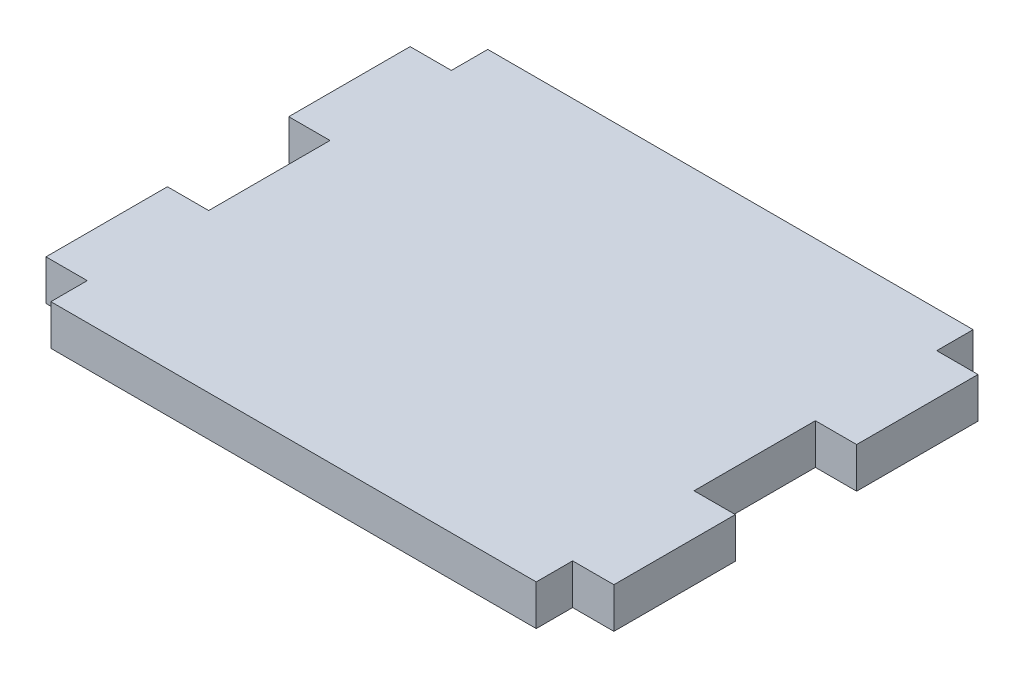
SolidWorks part; units mm, degrees
ref_plane "Front Plane" through (0, 0, 0) normal (0, 0, 1) x (1, 0, 0)
ref_plane "Top Plane" through (0, 0, 0) normal (0, 1, 0) x (1, 0, 0)
ref_plane "Right Plane" through (0, 0, 0) normal (1, 0, 0) x (0, 0, -1)
sketch "Sketch1" plane through (0, 0, 0) normal (1, 0, 0) x (0, 0, -1)
  line L1 (-27.0045, 2.5) -> (27.0045, 2.5)
  line L2 (-27.0045, 2.5) -> (-27.0045, -2.5)
  line L3 (-27.0045, -2.5) -> (27.0045, -2.5)
  line L4 (27.0045, 2.5) -> (27.0045, -2.5)
  line L5 (-27.0045, 2.5) -> (27.0045, -2.5) construction
  line L6 (-27.0045, -2.5) -> (27.0045, 2.5) construction
  point P0 (0, 0)
  dimension "D1" = 5
  dimension "D2" = 54.24
extrude "Boss-Extrude1" add sketch "Sketch1" along normal blind 70.2
sketch "Sketch5" plane through (0, -2.5, 0) normal (0, -1, 0) x (1, 0, 0)
  line L0 (70.2, 27.0045) -> (65.1, 27.0045)
  line L1 (70.2, 27.0045) -> (0, 27.0045) construction
  line L2 (65.1, 27.0045) -> (65.1, 22.5045)
  line L3 (65.1, 22.5045) -> (70.2, 22.5045)
  line L4 (70.2, 27.0045) -> (70.2, -27.0045) construction
  line L5 (70.2, 22.5045) -> (70.2, 27.0045)
  line L6 (70.2, -27.0045) -> (65.1, -27.0045)
  line L7 (70.2, -27.0045) -> (0, -27.0045) construction
  line L8 (65.1, -27.0045) -> (65.1, -22.5045)
  line L9 (65.1, -22.5045) -> (70.2, -22.5045)
  line L10 (70.2, -22.5045) -> (70.2, -27.0045)
  line L11 (70.2, 7.4955) -> (65.1, 7.4955)
  line L12 (65.1, 7.4955) -> (65.1, -7.5045)
  line L13 (65.1, -7.5045) -> (70.2, -7.5045)
  line L14 (70.2, -7.5045) -> (70.2, 7.4955)
  line L16 (5.1, -22.5045) -> (0, -22.5045)
  line L17 (5.1, -27.0045) -> (5.1, -22.5045)
  line L18 (0, -27.0045) -> (5.1, -27.0045)
  line L19 (0, -22.5045) -> (0, -27.0045)
  line L20 (5.1, -7.5045) -> (0, -7.5045)
  line L21 (0, -7.5045) -> (0, 7.4955)
  line L22 (5.1, 7.4955) -> (5.1, -7.5045)
  line L23 (0, 7.4955) -> (5.1, 7.4955)
  line L24 (5.1, 27.0045) -> (5.1, 22.5045)
  line L25 (0, 27.0045) -> (5.1, 27.0045)
  line L26 (0, 22.5045) -> (0, 27.0045)
  line L27 (5.1, 22.5045) -> (0, 22.5045)
  dimension "D1" = 5.1
  dimension "D2" = 4.5
  dimension "D3" = 5.1
  dimension "D4" = 4.5
  dimension "D5" = 15
  dimension "D6" = 5.1
  dimension "D7" = 15
extrude "Cut-Extrude1" cut sketch "Sketch5" against normal through all
